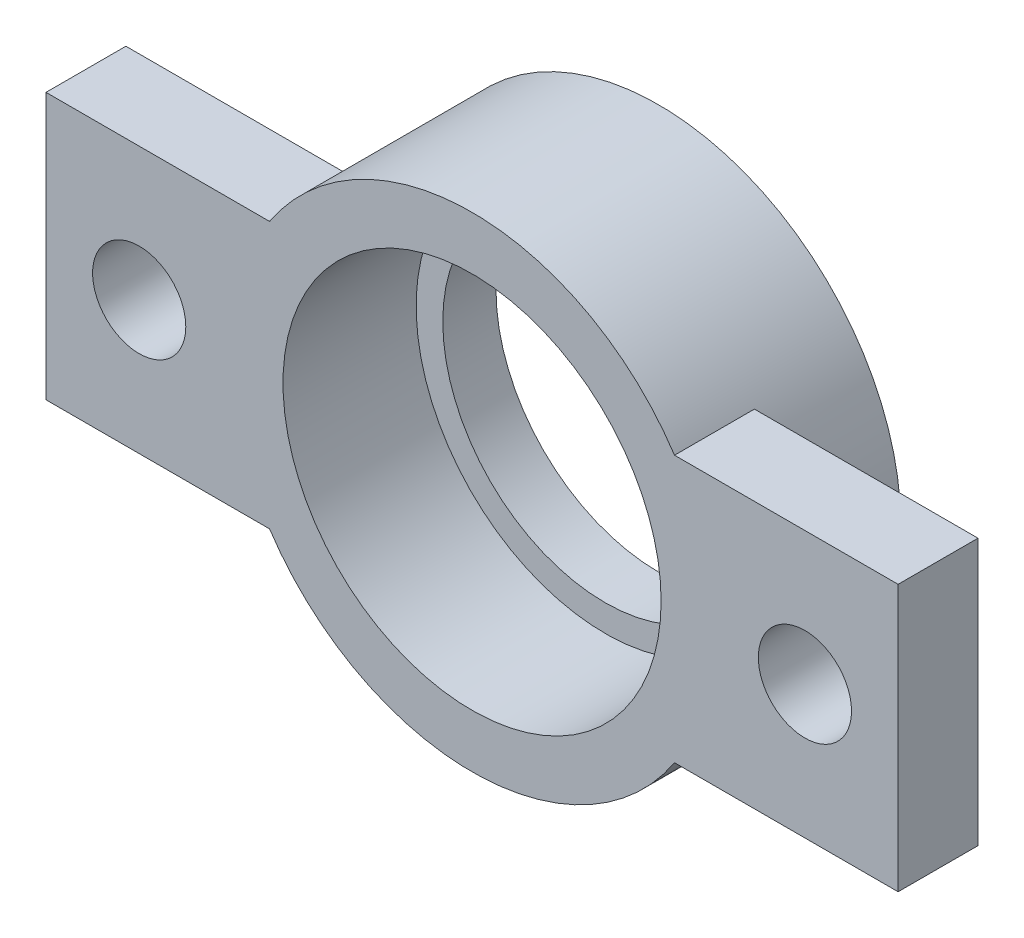
SolidWorks part; units mm, degrees
ref_plane "Спереди" through (0, 0, 0) normal (0, 0, 1) x (1, 0, 0)
ref_plane "Сверху" through (0, 0, 0) normal (0, 1, 0) x (1, 0, 0)
ref_plane "Справа" through (0, 0, 0) normal (1, 0, 0) x (0, 0, -1)
sketch "Эскиз1" plane through (0, 0, 0) normal (0, 0, 1) x (1, 0, 0)
  line L0 (0, -55) -> (0, 55) construction
  line L1 (-16, -5) -> (16, -5)
  line L2 (-16, -5) -> (-16, 5)
  line L3 (-16, 5) -> (16, 5)
  line L4 (16, -5) -> (16, 5)
  line L5 (-16, -5) -> (16, 5) construction
  line L6 (-16, 5) -> (16, -5) construction
  circle A0 centre (0, 0) radius 7.1
  circle A1 centre (0, 0) radius 9.1
  circle A2 centre (12.5, 0) radius 1.75
  circle A3 centre (-12.5, 0) radius 1.75
  dimension "D1" = 14.2
  dimension "D3" = 3.5
  dimension "D4" = 10
  dimension "D5" = 12.5
  dimension "D6" = 3.5
  dimension "D2" = 2
extrude "Бобышка-Вытянуть1" add sketch "Эскиз1" along normal blind 3 contours A1 L3 L2 L1 A3 | L3 A1 L1 A0 | L3 A1 A0 | L1 A1 L3 A0 | A1 L1 L4 L3 A2 | L1 A1 A0
sketch "Эскиз2" plane through (0, 0, 0) normal (0, 0, -1) x (-1, 0, 0)
  circle A0 centre (0, 0) radius 7.1 construction
  circle A1 centre (0, 0) radius 7.1
  circle A2 centre (0, 0) radius 9.1
  arc A3 (7.6033, 5) -> (-7.6033, 5) centre (0, 0) ccw construction
extrude "Бобышка-Вытянуть2" add sketch "Эскиз2" along normal blind 4
sketch "Эскиз3" plane through (0, 0, -4) normal (0, 0, 1) x (1, 0, 0)
  circle A0 centre (0, 0) radius 7.1 construction
  circle A1 centre (0, 0) radius 7.1
  circle A2 centre (0, 0) radius 6.1
  dimension "D1" = 1
extrude "Бобышка-Вытянуть3" add sketch "Эскиз3" along normal blind 2
